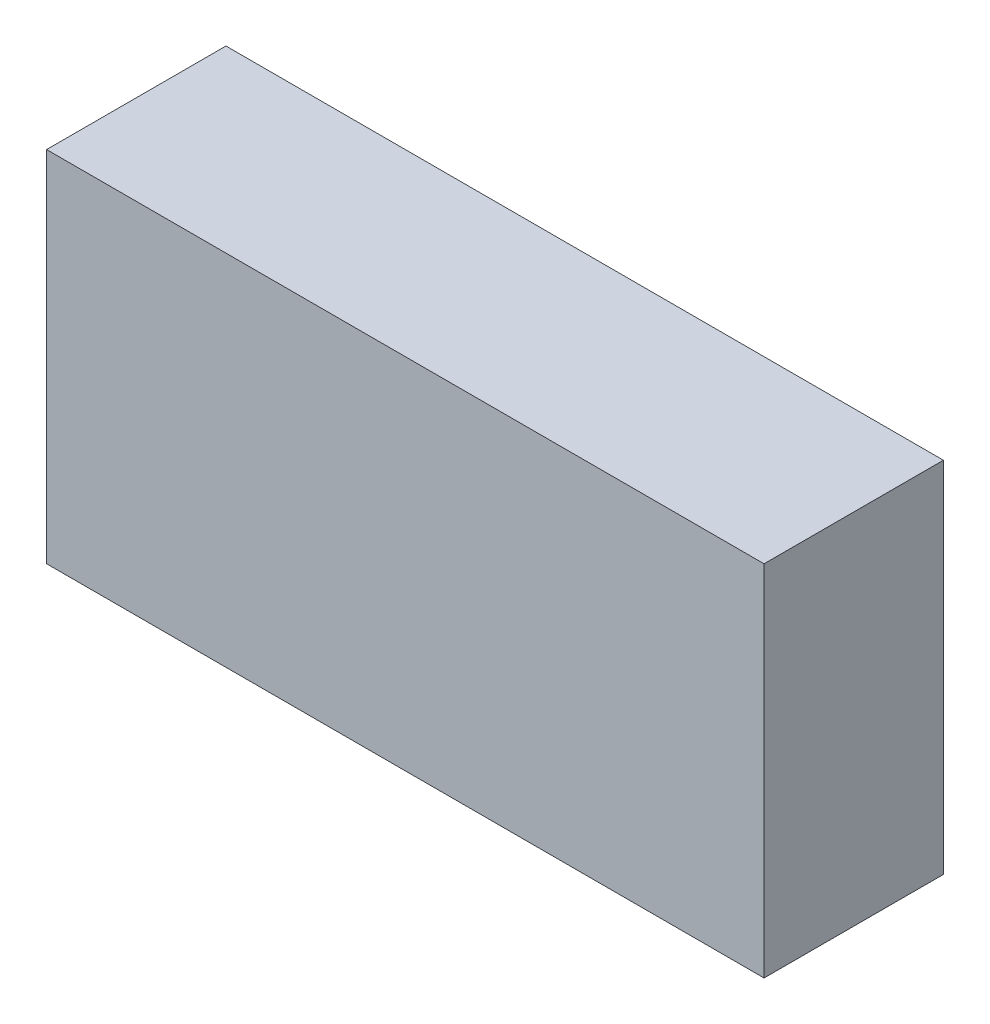
SolidWorks part; units mm, degrees
ref_plane "Front Plane" through (0, 0, 0) normal (0, 0, 1) x (1, 0, 0)
ref_plane "Top Plane" through (0, 0, 0) normal (0, 1, 0) x (1, 0, 0)
ref_plane "Right Plane" through (0, 0, 0) normal (1, 0, 0) x (0, 0, -1)
sketch "Sketch1" plane through (0, 0, 0) normal (0, 0, 1) x (1, 0, 0)
  line L0 (-20, -10) -> (20, -10)
  line L1 (20, -10) -> (20, 10)
  line L2 (20, 10) -> (-20, 10)
  line L3 (-20, 10) -> (-20, -10)
  dimension "D1" = 40
  dimension "D2" = 20
extrude "Boss-Extrude1" add sketch "Sketch1" along normal blind 10
sketch "Sketch2" plane through (0, 0, 0) normal (0, 0, 1) x (1, 0, 0)
  line L0 (-18, -5) -> (-12, -5)
  line L1 (-12, -5) -> (-12, 1)
  line L2 (-12, 1) -> (-18, 1)
  line L3 (-18, 1) -> (-18, -5)
  dimension "D1" = 6
  dimension "D2" = 6
extrude "Boss-Extrude2" add sketch "Sketch2" along normal blind 5
sketch "Sketch3" plane through (0, 0, 0) normal (0, 0, 1) x (1, 0, 0)
  line L0 (-9, -5) -> (-3, -5)
  line L1 (-3, -5) -> (-3, 1)
  line L2 (-3, 1) -> (-9, 1)
  line L3 (-9, 1) -> (-9, -5)
  dimension "D1" = 6
  dimension "D2" = 6
extrude "Boss-Extrude3" add sketch "Sketch3" along normal blind 6
sketch "Sketch4" plane through (0, 0, 0) normal (0, 0, 1) x (1, 0, 0)
  line L0 (0, -5) -> (6, -5)
  line L1 (6, -5) -> (6, 1)
  line L2 (6, 1) -> (0, 1)
  line L3 (0, 1) -> (0, -5)
  dimension "D1" = 6
  dimension "D2" = 6
extrude "Boss-Extrude4" add sketch "Sketch4" along normal blind 7
